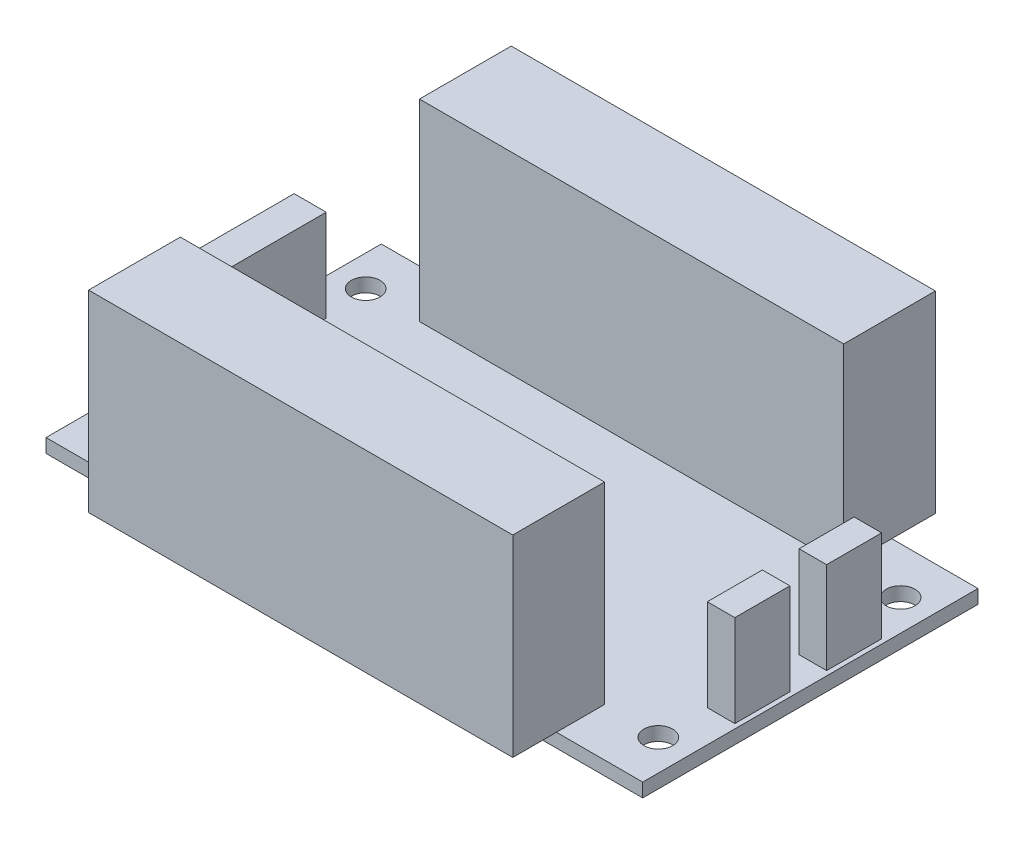
SolidWorks part; units mm, degrees
ref_plane "Front Plane" through (0, 0, 0) normal (0, 0, 1) x (1, 0, 0)
ref_plane "Top Plane" through (0, 0, 0) normal (0, 1, 0) x (1, 0, 0)
ref_plane "Right Plane" through (0, 0, 0) normal (1, 0, 0) x (0, 0, -1)
sketch "Sketch1" plane through (0, 0, 0) normal (0, 1, 0) x (1, 0, 0)
  line L0 (0, 0) -> (0, 8.2053) construction
  line L1 (-32.515, -18.27) -> (32.515, -18.27)
  line L2 (-32.515, -18.27) -> (-32.515, 18.27)
  line L3 (-32.515, 18.27) -> (32.515, 18.27)
  line L4 (32.515, -18.27) -> (32.515, 18.27)
  line L5 (-32.515, -18.27) -> (32.515, 18.27) construction
  line L6 (-32.515, 18.27) -> (32.515, -18.27) construction
  line L7 (0, 0) -> (7.9638, 0) construction
  circle A0 centre (-29.145, 13.2) radius 1.57
  circle A1 centre (29.145, 13.2) radius 1.57
  circle A2 centre (29.145, -13.2) radius 1.57
  circle A3 centre (-29.145, -13.2) radius 1.57
  point P0 (0, 0)
  dimension "D3" = 3.14
  dimension "D4" = 3.37
  dimension "D5" = 5.07
  dimension "D1" = 65.03
  dimension "D2" = 36.54
extrude "Boss-Extrude1" add sketch "Sketch1" along normal blind 1.5
sketch "Sketch2" plane through (0, 1.5, 0) normal (0, 1, 0) x (1, 0, 0)
  line L1 (32.015, -1.73) -> (32.015, -7.73)
  line L2 (-28.515, 8.27) -> (-28.515, -7.73)
  line L5 (32.015, 2.27) -> (29.015, 2.27)
  line L6 (32.015, 8.27) -> (29.015, 8.27)
  line L8 (29.015, 8.27) -> (29.015, 2.27)
  line L11 (32.015, -1.73) -> (29.015, -1.73)
  line L12 (29.015, -1.73) -> (29.015, -7.73)
  line L13 (29.015, -7.73) -> (32.015, -7.73)
  line L15 (-28.515, -7.73) -> (-32.015, -7.73)
  line L16 (-32.015, -7.73) -> (-32.015, 8.27)
  line L17 (32.515, -18.27) -> (32.515, 18.27) construction
  line L18 (-32.015, 8.27) -> (-28.515, 8.27)
  line L19 (-32.515, 18.27) -> (-32.515, -18.27) construction
  line L20 (32.515, 18.27) -> (-32.515, 18.27) construction
  line L21 (32.015, 8.27) -> (32.015, 2.27)
  dimension "D1" = 16
  dimension "D2" = 0.5
  dimension "D3" = 3.5
  dimension "D4" = 0.5
  dimension "D5" = 6
  dimension "D6" = 6
  dimension "D7" = 3
  dimension "D8" = 10
  dimension "D9" = 4
extrude "Boss-Extrude2" add sketch "Sketch2" along normal blind 10
sketch "Sketch3" plane through (0, 1.5, 0) normal (0, 1, 0) x (1, 0, 0)
  line L0 (0, 0) -> (9.0826, 0) construction
  line L1 (-23.115, -13.0309) -> (23.115, -13.0309)
  line L2 (-23.115, -13.0309) -> (-23.115, -23.0309)
  line L3 (-23.115, -23.0309) -> (23.115, -23.0309)
  line L4 (23.115, -13.0309) -> (23.115, -23.0309)
  line L5 (23.115, 13.0309) -> (23.115, 23.0309)
  line L6 (-23.115, 23.0309) -> (23.115, 23.0309)
  line L7 (-23.115, 13.0309) -> (-23.115, 23.0309)
  line L8 (-23.115, 13.0309) -> (23.115, 13.0309)
  line L9 (-32.515, 18.27) -> (-32.515, -18.27) construction
  line L10 (32.515, -18.27) -> (32.515, 18.27) construction
  dimension "D1" = 9.4
  dimension "D2" = 10
  dimension "D3" = 9.4
extrude "Boss-Extrude3" add sketch "Sketch3" along normal blind 21
